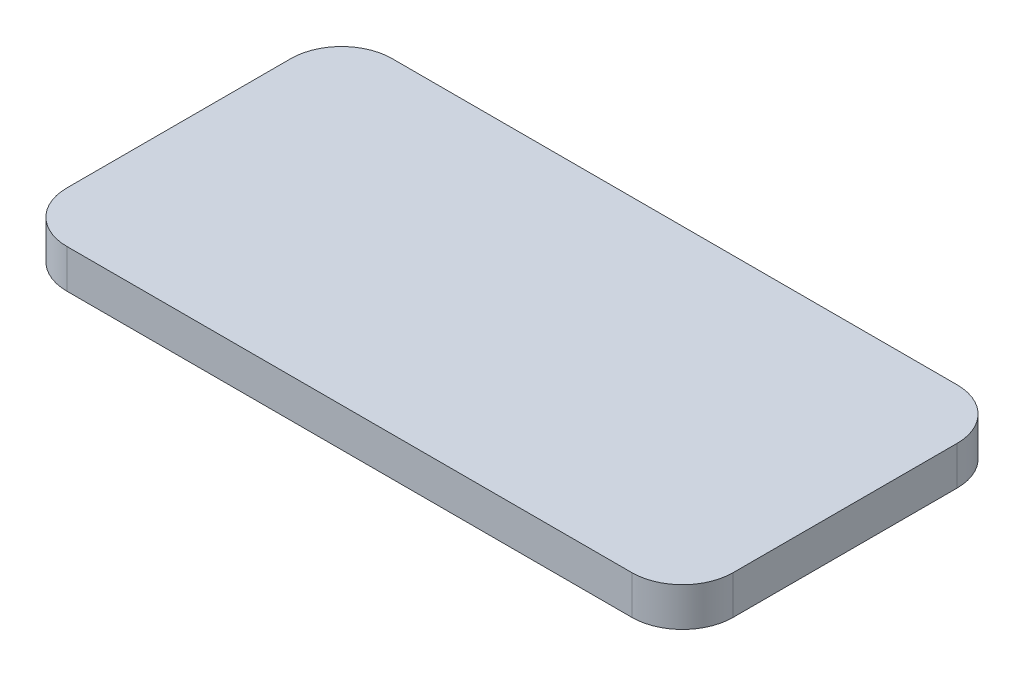
SolidWorks part; units mm, degrees
ref_plane "前视基准面" through (0, 0, 0) normal (0, 0, 1) x (1, 0, 0)
ref_plane "上视基准面" through (0, 0, 0) normal (0, 1, 0) x (1, 0, 0)
ref_plane "右视基准面" through (0, 0, 0) normal (1, 0, 0) x (0, 0, -1)
sketch "草图1" plane through (0, 0, 0) normal (0, 1, 0) x (1, 0, 0)
  line L1 (-65.75, -32.1) -> (65.75, -32.1)
  line L2 (-65.75, -32.1) -> (-65.75, 32.1)
  line L3 (-65.75, 32.1) -> (65.75, 32.1)
  line L4 (65.75, -32.1) -> (65.75, 32.1)
  line L5 (-65.75, -32.1) -> (65.75, 32.1) construction
  line L6 (-65.75, 32.1) -> (65.75, -32.1) construction
  point P0 (0, 0)
  dimension "D1" = 64.2
  dimension "D2" = 131.5
extrude "凸台-拉伸1" add sketch "草图1" along normal blind 7.65
fillet "圆角1" radius 10 4 edges at (-65.75, 3.825, -32.1) (65.75, 3.825, -32.1) (65.75, 3.825, 32.1) (-65.75, 3.825, 32.1)
